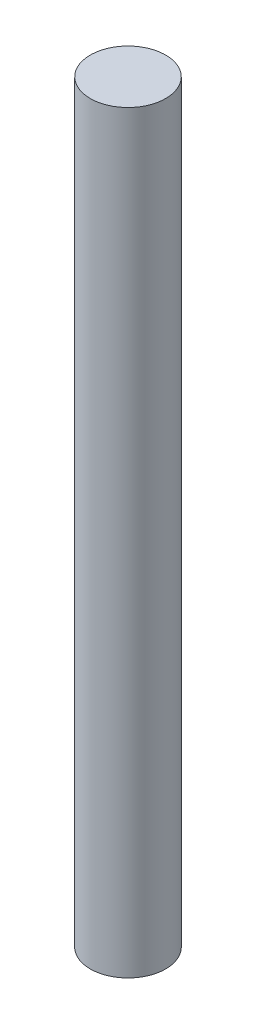
SolidWorks part; units mm, degrees
ref_plane "前视基准面" through (0, 0, 0) normal (0, 0, 1) x (1, 0, 0)
ref_plane "上视基准面" through (0, 0, 0) normal (0, 1, 0) x (1, 0, 0)
ref_plane "右视基准面" through (0, 0, 0) normal (1, 0, 0) x (0, 0, -1)
sketch "草图1" plane through (0, 0, 0) normal (0, 1, 0) x (1, 0, 0)
  circle A0 centre (0, 0) radius 2.5
extrude "凸台-拉伸1" add sketch "草图1" along normal blind 50
